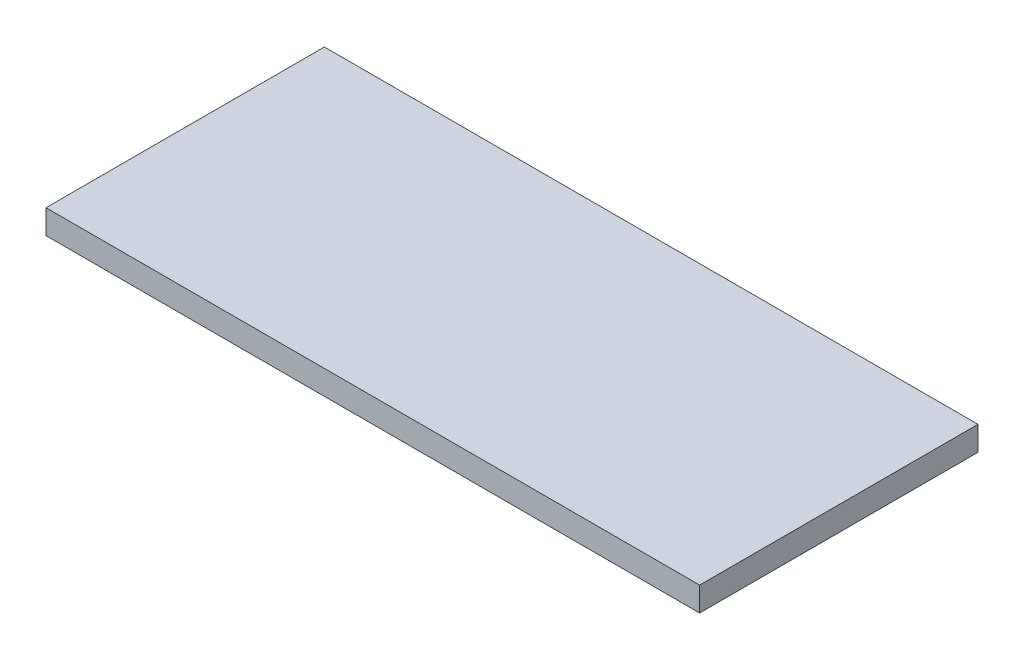
SolidWorks part; units mm, degrees
ref_plane "前视基准面" through (0, 0, 0) normal (0, 0, 1) x (1, 0, 0)
ref_plane "上视基准面" through (0, 0, 0) normal (0, 1, 0) x (1, 0, 0)
ref_plane "右视基准面" through (0, 0, 0) normal (1, 0, 0) x (0, 0, -1)
sketch "草图1" plane through (0, 0, 0) normal (0, 1, 0) x (1, 0, 0)
  line L1 (-27, -11.5) -> (27, -11.5)
  line L2 (-27, -11.5) -> (-27, 11.5)
  line L3 (-27, 11.5) -> (27, 11.5)
  line L4 (27, -11.5) -> (27, 11.5)
  line L5 (-27, -11.5) -> (27, 11.5) construction
  line L6 (-27, 11.5) -> (27, -11.5) construction
  point P0 (0, 0)
  dimension "D1" = 54
  dimension "D2" = 23
extrude "凸台-拉伸1" add sketch "草图1" along normal blind 2
